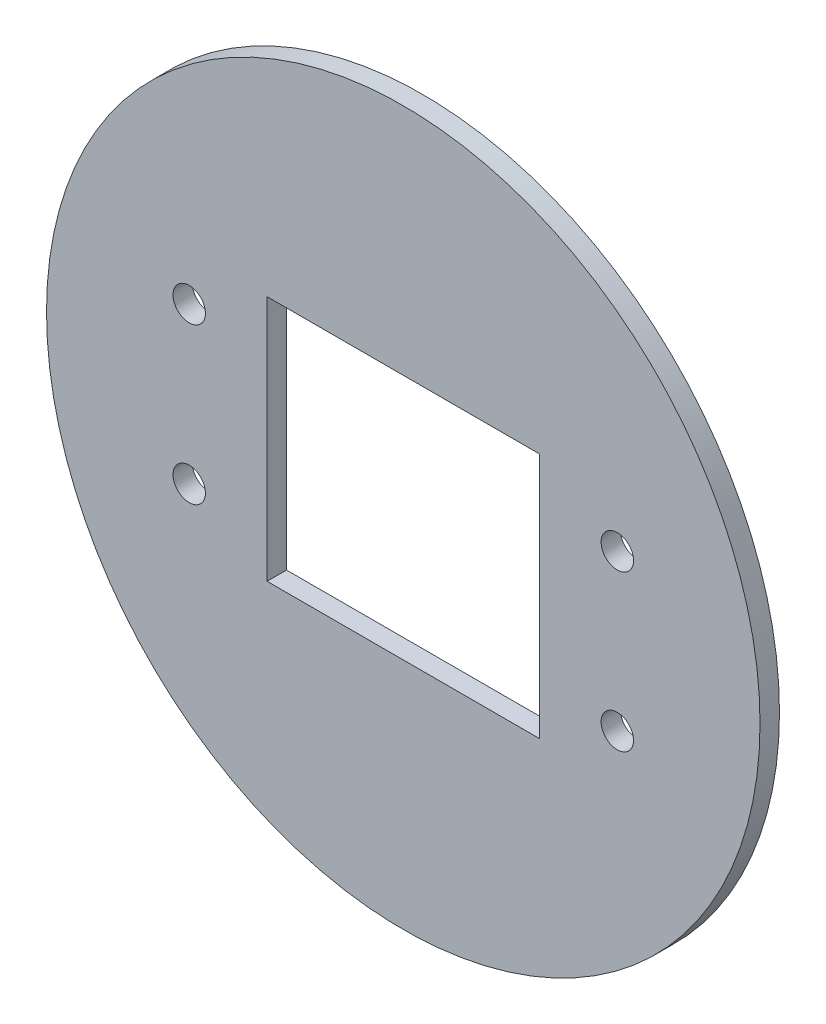
SolidWorks part; units mm, degrees
ref_plane "前视基准面" through (0, 0, 0) normal (0, 0, 1) x (1, 0, 0)
ref_plane "上视基准面" through (0, 0, 0) normal (0, 1, 0) x (1, 0, 0)
ref_plane "右视基准面" through (0, 0, 0) normal (1, 0, 0) x (0, 0, -1)
sketch "草图2" plane through (0, 0, 0) normal (0, 0, 1) x (1, 0, 0)
  line L1 (-10.5, 9.5) -> (10.5, 9.5)
  line L2 (-10.5, 9.5) -> (-10.5, -9.5)
  line L3 (-10.5, -9.5) -> (10.5, -9.5)
  line L4 (10.5, 9.5) -> (10.5, -9.5)
  line L5 (-10.5, 9.5) -> (10.5, -9.5) construction
  line L6 (-10.5, -9.5) -> (10.5, 9.5) construction
  circle A0 centre (0, 0) radius 27.5
  dimension "D1" = 55
  dimension "D2" = 19
  dimension "D3" = 21
extrude "凸台-拉伸2" add sketch "草图2" along normal blind 1.5 contours L2 L3 L4 L1 | A0
sketch "草图3" plane through (0, 0, 1.5) normal (0, 0, 1) x (1, 0, 0)
  line L0 (10.5, 9.5) -> (10.5, -9.5) construction
  line L2 (0.825, 0) -> (-0.825, 0) construction
  line L3 (0, -0.825) -> (0, 0.825) construction
  circle A0 centre (16.5, 6) radius 1.25
  circle A1 centre (-16.5, 6) radius 1.25
  circle A2 centre (16.5, -6) radius 1.25
  circle A3 centre (-16.5, -6) radius 1.25
  dimension "D1" = 6
  dimension "D2" = 6
extrude "切除-拉伸1" cut sketch "草图3" against normal blind 10
